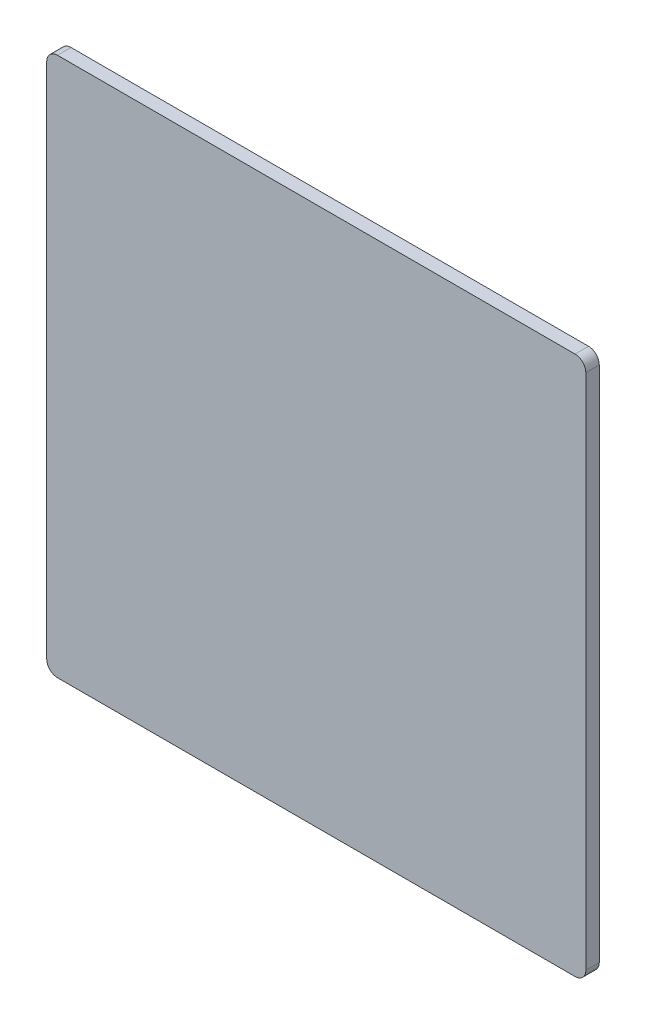
SolidWorks part; units mm, degrees
material "Glass"
ref_plane "Front Plane" through (0, 0, 0) normal (0, 0, 1) x (1, 0, 0)
ref_plane "Top Plane" through (0, 0, 0) normal (0, 1, 0) x (1, 0, 0)
ref_plane "Right Plane" through (0, 0, 0) normal (1, 0, 0) x (0, 0, -1)
sketch "Sketch1" plane through (0, 0, 0) normal (0, 0, 1) x (1, 0, 0)
  line L1 (-100, -100) -> (100, -100)
  line L2 (-100, -100) -> (-100, 100)
  line L3 (-100, 100) -> (100, 100)
  line L4 (100, -100) -> (100, 100)
  line L5 (-100, -100) -> (100, 100) construction
  line L6 (-100, 100) -> (100, -100) construction
  point P0 (0, 0)
  dimension "D1" = 200
  dimension "D2" = 200
extrude "Boss-Extrude1" add sketch "Sketch1" along normal blind 5
fillet "Fillet1" radius 4 4 edges at (-100, -100, 2.5) (100, -100, 2.5) (100, 100, 2.5) (-100, 100, 2.5)
